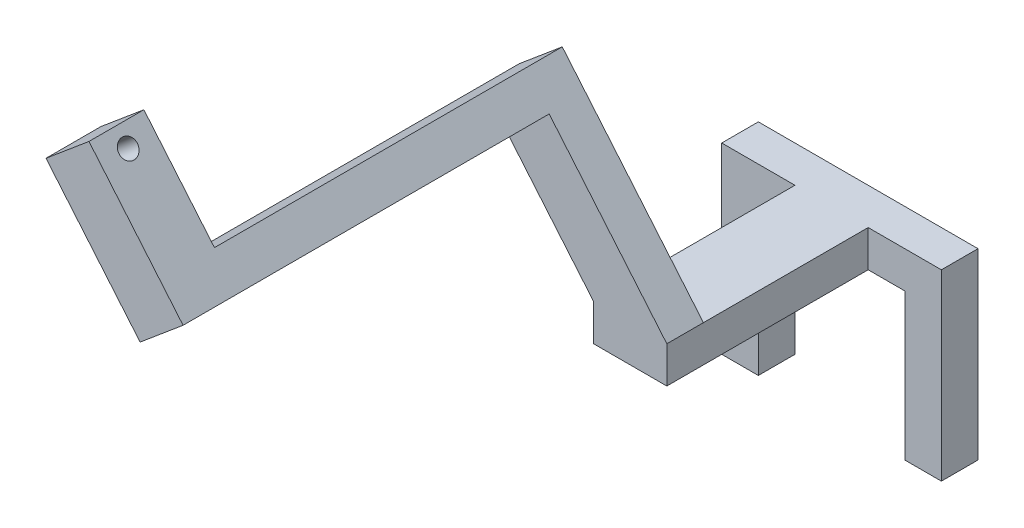
SolidWorks part; units mm, degrees
ref_plane "Přední rovina" through (0, 0, 0) normal (0, 0, 1) x (1, 0, 0)
ref_plane "Horní rovina" through (0, 0, 0) normal (0, 1, 0) x (1, 0, 0)
ref_plane "Pravá rovina" through (0, 0, 0) normal (1, 0, 0) x (0, 0, -1)
sketch "Skica1" plane through (0, 0, 0) normal (0, 0, 1) x (1, 0, 0)
  line L0 (0, 0) -> (60, 0)
  line L1 (60, 0) -> (60, -50)
  line L2 (60, -50) -> (50, -50)
  line L3 (50, -50) -> (50, -10)
  line L4 (50, -10) -> (10, -10)
  line L5 (10, -10) -> (10, -50)
  line L6 (10, -50) -> (0, -50)
  line L7 (0, -50) -> (0, 0)
  dimension "D1" = 60
  dimension "D2" = 40
  dimension "D3" = 10
  dimension "D4" = 10
  dimension "D5" = 40
  dimension "D6" = 40
  dimension "D7" = 10
extrude "Přidat vysunutím1" add sketch "Skica1" along normal blind 10
sketch "Skica2" plane through (0, 0, 10) normal (0, 0, 1) x (1, 0, 0)
  line L0 (60, 0) -> (0, 0) construction
  line L1 (20, 0) -> (40, 0)
  line L2 (20, 0) -> (20, -10)
  line L3 (20, -10) -> (40, -10)
  line L4 (40, 0) -> (40, -10)
  line L5 (10, -10) -> (50, -10) construction
  line L6 (0, 0) -> (0, -50) construction
  dimension "D1" = 20
  dimension "D2" = 20
extrude "Přidat vysunutím2" add sketch "Skica2" along normal blind 55
sketch "Skica3" plane through (0, 0, 65) normal (0, 0, 1) x (1, 0, 0)
  line L0 (40, 0) -> (7.8606, 38.3022)
  line L1 (7.8606, 38.3022) -> (-3.8759, 28.4541)
  line L2 (-3.8759, 28.4541) -> (20, 0)
  line L3 (20, 0) -> (0, 0) construction
  line L4 (20, 0) -> (40, 0)
  dimension "D1" = 50
  dimension "D2" = 15.3209
  dimension "D3" = 50
extrude "Přidat vysunutím3" add sketch "Skica3" against normal blind 10
sketch "Skica4" plane through (-15.6123, 18.6061, 0) normal (-0.6428, 0.766, 0) x (0.766, 0.6428, 0)
  line L0 (30.6418, -55) -> (30.6418, -65) construction
  line L1 (15.3209, -55) -> (30.6418, -55)
  line L2 (15.3209, -55) -> (15.3209, -165)
  line L3 (15.3209, -165) -> (30.6418, -165)
  line L4 (30.6418, -55) -> (30.6418, -165)
  dimension "D1" = 110
extrude "Přidat vysunutím4" add sketch "Skica4" along normal blind 10
sketch "Skica5" plane through (-22.0402, 26.2665, 0) normal (-0.6428, 0.766, 0) x (0.766, 0.6428, 0)
  line L0 (15.3209, -55) -> (15.3209, -165) construction
  line L1 (30.6418, -165) -> (15.3209, -165)
  line L2 (30.6418, -165) -> (30.6418, -150)
  line L3 (30.6418, -150) -> (15.3209, -150)
  line L4 (15.3209, -165) -> (15.3209, -150)
  dimension "D1" = 15
extrude "Přidat vysunutím5" add sketch "Skica5" along normal blind 30
sketch "Skica6" plane through (23.473, 19.6962, 0) normal (0.766, 0.6428, 0) x (0, 0, -1)
  line L0 (-165, 64.2885) -> (-150, 64.2885) construction
  line L1 (-165, 64.2885) -> (-165, 24.2885) construction
  circle A0 centre (-157.5, 59.2885) radius 2.5
  dimension "D1" = 5
  dimension "D2" = 5
  dimension "D3" = 7.5
extrude "Odebrat vysunutím1" cut sketch "Skica6" against normal through all
